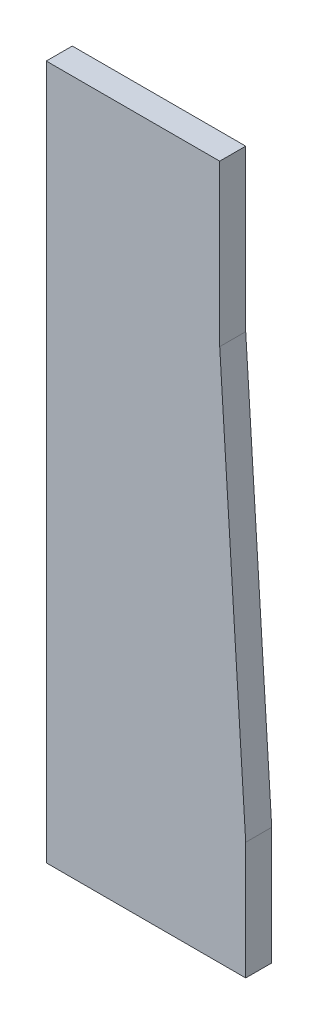
SolidWorks part; units mm, degrees
material "MDF"
ref_plane "Front Plane" through (0, 0, 0) normal (0, 0, 1) x (1, 0, 0)
ref_plane "Top Plane" through (0, 0, 0) normal (0, 1, 0) x (1, 0, 0)
ref_plane "Right Plane" through (0, 0, 0) normal (1, 0, 0) x (0, 0, -1)
sketch "Sketch1" plane through (0, 0, 0) normal (0, 0, 1) x (1, 0, 0)
  line L0 (82.0395, -5024.8784) -> (82.0395, -5533.4155)
  line L1 (82.0395, -5024.8784) -> (82.0395, -5464.9635) construction
  line L8 (-209.0395, -5024.8784) -> (-209.0395, -5142.5528)
  line L11 (-228.0888, -5533.4155) -> (228.0888, -5533.4155)
  line L14 (209.0395, -5142.5528) -> (209.0395, -5024.8784)
  line L15 (209.0395, -5024.8784) -> (-209.0395, -5024.8784)
  line L22 (209.0395, -5142.5528) -> (209.0395, -5024.8784)
  line L23 (209.0395, -5024.8784) -> (82.0395, -5024.8784)
  line L106 (82.0395, -5533.4155) -> (228.0888, -5533.4155)
  line L119 (-209.0395, -5142.5528) -> (-228.0888, -5447.3417)
  line L120 (-228.0888, -5447.3417) -> (-228.0888, -5533.4155)
  line L121 (228.0888, -5533.4155) -> (228.0888, -5447.3417)
  line L122 (228.0888, -5533.4155) -> (228.0888, -5447.3417)
  line L123 (228.0888, -5447.3417) -> (209.0395, -5142.5528)
  line L124 (228.0888, -5447.3417) -> (209.0395, -5142.5528)
  point P10 (82.0395, -5520.6085)
  dimension "D1" = 0
extrude "Boss-Extrude1" add sketch "Sketch1" along normal blind 19.05
